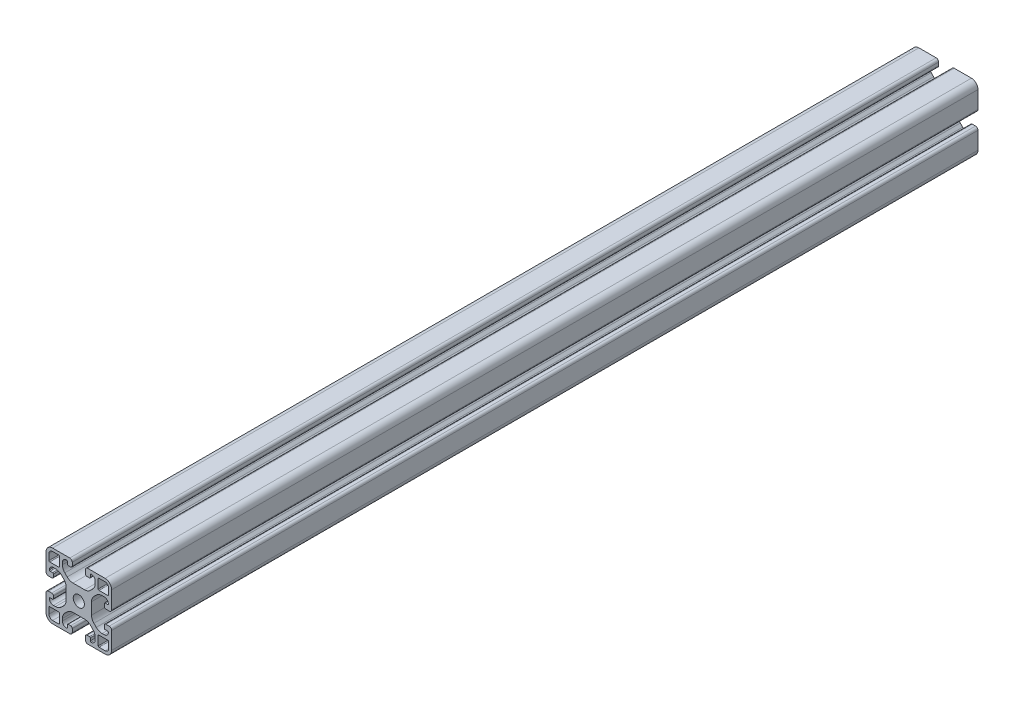
SolidWorks part; units mm, degrees
ref_plane "Plan de face" through (0, 0, 0) normal (0, 0, 1) x (1, 0, 0)
ref_plane "Plan de dessus" through (0, 0, 0) normal (0, 1, 0) x (1, 0, 0)
ref_plane "Plan de droite" through (0, 0, 0) normal (1, 0, 0) x (0, 0, -1)
ref_plane "Plan1" through (0, 0, -30) normal (0, 0, -1) x (-1, 0, 0)
sketch "Esquisse1" plane through (0, 0, -30) normal (0, 0, -1) x (-1, 0, 0)
  line B0 (-4.5, 15) -> (-4.5, 13.5)
  line B1 (-4, 13) -> (-2.5, 13)
  line B2 (-4.5, 10) -> (-5.8076, 10)
  line B3 (-9.3431, 11.4645) -> (-10.7855, 12.9069)
  line B4 (-12.25, 16.4424) -> (-12.25, 23.5576)
  line B5 (-10.7855, 27.0931) -> (-9.3431, 28.5355)
  line B6 (-5.8076, 30) -> (-4.5, 30)
  line B7 (-2.5, 27) -> (-4, 27)
  line B8 (-4.5, 26.5) -> (-4.5, 25)
  line B9 (-3.5, 24) -> (-1.5, 24)
  line B10 (0, 25.5) -> (0, 36)
  line B11 (-4, 40) -> (-14.5, 40)
  line B12 (-16, 38.5) -> (-16, 36.5)
  line B13 (-15, 35.5) -> (-13.5, 35.5)
  line B14 (-13, 36) -> (-13, 37.5)
  line B15 (-10, 35.5) -> (-10, 34.1924)
  line B16 (-11.4645, 30.6569) -> (-12.9069, 29.2145)
  line B17 (-16.4424, 27.75) -> (-23.5576, 27.75)
  line B18 (-27.0931, 29.2145) -> (-28.5355, 30.6569)
  line B19 (-30, 34.1924) -> (-30, 35.5)
  line B20 (-27, 37.5) -> (-27, 36)
  line B21 (-26.5, 35.5) -> (-25, 35.5)
  line B22 (-24, 36.5) -> (-24, 38.5)
  line B23 (-25.5, 40) -> (-36, 40)
  line B24 (-40, 36) -> (-40, 25.5)
  line B25 (-38.5, 24) -> (-36.5, 24)
  line B26 (-35.5, 25) -> (-35.5, 26.5)
  line B27 (-36, 27) -> (-37.5, 27)
  line B28 (-35.5, 30) -> (-34.1924, 30)
  line B29 (-30.6569, 28.5355) -> (-29.2145, 27.0931)
  line B30 (-27.75, 23.5576) -> (-27.75, 16.4424)
  line B31 (-29.2145, 12.9069) -> (-30.6569, 11.4645)
  line B32 (-34.1924, 10) -> (-35.5, 10)
  line B33 (-37.5, 13) -> (-36, 13)
  line B34 (-35.5, 13.5) -> (-35.5, 15)
  line B35 (-36.5, 16) -> (-38.5, 16)
  line B36 (-40, 14.5) -> (-40, 4)
  line B37 (-36, 0) -> (-25.5, 0)
  line B38 (-24, 1.5) -> (-24, 3.5)
  line B39 (-25, 4.5) -> (-26.5, 4.5)
  line B40 (-27, 4) -> (-27, 2.5)
  line B41 (-30, 4.5) -> (-30, 5.8076)
  line B42 (-28.5355, 9.3431) -> (-27.0931, 10.7855)
  line B43 (-23.5576, 12.25) -> (-16.4424, 12.25)
  line B44 (-12.9069, 10.7855) -> (-11.4645, 9.3431)
  line B45 (-10, 5.8076) -> (-10, 4.5)
  line B46 (-13, 2.5) -> (-13, 4)
  line B47 (-13.5, 4.5) -> (-15, 4.5)
  line B48 (-16, 3.5) -> (-16, 1.5)
  line B49 (-14.5, 0) -> (-4, 0)
  line B50 (0, 4) -> (0, 14.5)
  line B51 (-1.5, 16) -> (-3.5, 16)
  line B52 (-4, 1.8) -> (-7.7, 1.8)
  line B53 (-8.2, 2.3) -> (-8.2, 7.7)
  line B54 (-7.7, 8.2) -> (-2.3, 8.2)
  line B55 (-1.8, 7.7) -> (-1.8, 4)
  line B56 (-38.2, 4) -> (-38.2, 7.7)
  line B57 (-37.7, 8.2) -> (-32.3, 8.2)
  line B58 (-31.8, 7.7) -> (-31.8, 2.3)
  line B59 (-32.3, 1.8) -> (-36, 1.8)
  line B60 (-36, 38.2) -> (-32.3, 38.2)
  line B61 (-31.8, 37.7) -> (-31.8, 32.3)
  line B62 (-32.3, 31.8) -> (-37.7, 31.8)
  line B63 (-38.2, 32.3) -> (-38.2, 36)
  line B64 (-1.8, 36) -> (-1.8, 32.3)
  line B65 (-2.3, 31.8) -> (-7.7, 31.8)
  line B66 (-8.2, 32.3) -> (-8.2, 37.7)
  line B67 (-7.7, 38.2) -> (-4, 38.2)
  arc B68 (-4.5, 13.5) -> (-4, 13) centre (-4, 13.5) ccw
  arc B69 (-2.5, 13) -> (-2, 12.5) centre (-2.5, 12.5) cw
  arc B70 (-2, 12.5) -> (-4.5, 10) centre (-4.5, 12.5) cw
  arc B71 (-5.8076, 10) -> (-9.3431, 11.4645) centre (-5.8076, 15) cw
  arc B72 (-10.7855, 12.9069) -> (-12.25, 16.4424) centre (-7.25, 16.4424) cw
  arc B73 (-12.25, 23.5576) -> (-10.7855, 27.0931) centre (-7.25, 23.5576) cw
  arc B74 (-9.3431, 28.5355) -> (-5.8076, 30) centre (-5.8076, 25) cw
  arc B75 (-4.5, 30) -> (-2, 27.5) centre (-4.5, 27.5) cw
  arc B76 (-2, 27.5) -> (-2.5, 27) centre (-2.5, 27.5) cw
  arc B77 (-4, 27) -> (-4.5, 26.5) centre (-4, 26.5) ccw
  arc B78 (-4.5, 25) -> (-3.5, 24) centre (-3.5, 25) ccw
  arc B79 (-1.5, 24) -> (0, 25.5) centre (-1.5, 25.5) ccw
  arc B80 (0, 36) -> (-4, 40) centre (-4, 36) ccw
  arc B81 (-14.5, 40) -> (-16, 38.5) centre (-14.5, 38.5) ccw
  arc B82 (-16, 36.5) -> (-15, 35.5) centre (-15, 36.5) ccw
  arc B83 (-13.5, 35.5) -> (-13, 36) centre (-13.5, 36) ccw
  arc B84 (-13, 37.5) -> (-12.5, 38) centre (-12.5, 37.5) cw
  arc B85 (-12.5, 38) -> (-10, 35.5) centre (-12.5, 35.5) cw
  arc B86 (-10, 34.1924) -> (-11.4645, 30.6569) centre (-15, 34.1924) cw
  arc B87 (-12.9069, 29.2145) -> (-16.4424, 27.75) centre (-16.4424, 32.75) cw
  arc B88 (-23.5576, 27.75) -> (-27.0931, 29.2145) centre (-23.5576, 32.75) cw
  arc B89 (-28.5355, 30.6569) -> (-30, 34.1924) centre (-25, 34.1924) cw
  arc B90 (-30, 35.5) -> (-27.5, 38) centre (-27.5, 35.5) cw
  arc B91 (-27.5, 38) -> (-27, 37.5) centre (-27.5, 37.5) cw
  arc B92 (-27, 36) -> (-26.5, 35.5) centre (-26.5, 36) ccw
  arc B93 (-25, 35.5) -> (-24, 36.5) centre (-25, 36.5) ccw
  arc B94 (-24, 38.5) -> (-25.5, 40) centre (-25.5, 38.5) ccw
  arc B95 (-36, 40) -> (-40, 36) centre (-36, 36) ccw
  arc B96 (-40, 25.5) -> (-38.5, 24) centre (-38.5, 25.5) ccw
  arc B97 (-36.5, 24) -> (-35.5, 25) centre (-36.5, 25) ccw
  arc B98 (-35.5, 26.5) -> (-36, 27) centre (-36, 26.5) ccw
  arc B99 (-37.5, 27) -> (-38, 27.5) centre (-37.5, 27.5) cw
  arc B100 (-38, 27.5) -> (-35.5, 30) centre (-35.5, 27.5) cw
  arc B101 (-34.1924, 30) -> (-30.6569, 28.5355) centre (-34.1924, 25) cw
  arc B102 (-29.2145, 27.0931) -> (-27.75, 23.5576) centre (-32.75, 23.5576) cw
  arc B103 (-27.75, 16.4424) -> (-29.2145, 12.9069) centre (-32.75, 16.4424) cw
  arc B104 (-30.6569, 11.4645) -> (-34.1924, 10) centre (-34.1924, 15) cw
  arc B105 (-35.5, 10) -> (-38, 12.5) centre (-35.5, 12.5) cw
  arc B106 (-38, 12.5) -> (-37.5, 13) centre (-37.5, 12.5) cw
  arc B107 (-36, 13) -> (-35.5, 13.5) centre (-36, 13.5) ccw
  arc B108 (-35.5, 15) -> (-36.5, 16) centre (-36.5, 15) ccw
  arc B109 (-38.5, 16) -> (-40, 14.5) centre (-38.5, 14.5) ccw
  arc B110 (-40, 4) -> (-36, 0) centre (-36, 4) ccw
  arc B111 (-25.5, 0) -> (-24, 1.5) centre (-25.5, 1.5) ccw
  arc B112 (-24, 3.5) -> (-25, 4.5) centre (-25, 3.5) ccw
  arc B113 (-26.5, 4.5) -> (-27, 4) centre (-26.5, 4) ccw
  arc B114 (-27, 2.5) -> (-27.5, 2) centre (-27.5, 2.5) cw
  arc B115 (-27.5, 2) -> (-30, 4.5) centre (-27.5, 4.5) cw
  arc B116 (-30, 5.8076) -> (-28.5355, 9.3431) centre (-25, 5.8076) cw
  arc B117 (-27.0931, 10.7855) -> (-23.5576, 12.25) centre (-23.5576, 7.25) cw
  arc B118 (-16.4424, 12.25) -> (-12.9069, 10.7855) centre (-16.4424, 7.25) cw
  arc B119 (-11.4645, 9.3431) -> (-10, 5.8076) centre (-15, 5.8076) cw
  arc B120 (-10, 4.5) -> (-12.5, 2) centre (-12.5, 4.5) cw
  arc B121 (-12.5, 2) -> (-13, 2.5) centre (-12.5, 2.5) cw
  arc B122 (-13, 4) -> (-13.5, 4.5) centre (-13.5, 4) ccw
  arc B123 (-15, 4.5) -> (-16, 3.5) centre (-15, 3.5) ccw
  arc B124 (-16, 1.5) -> (-14.5, 0) centre (-14.5, 1.5) ccw
  arc B125 (-4, 0) -> (0, 4) centre (-4, 4) ccw
  arc B126 (0, 14.5) -> (-1.5, 16) centre (-1.5, 14.5) ccw
  arc B127 (-3.5, 16) -> (-4.5, 15) centre (-3.5, 15) ccw
  circle B128 centre (-20, 20) radius 3.4
  arc B129 (-1.8, 4) -> (-4, 1.8) centre (-4, 4) cw
  arc B130 (-7.7, 1.8) -> (-8.2, 2.3) centre (-7.7, 2.3) cw
  arc B131 (-8.2, 7.7) -> (-7.7, 8.2) centre (-7.7, 7.7) cw
  arc B132 (-2.3, 8.2) -> (-1.8, 7.7) centre (-2.3, 7.7) cw
  arc B133 (-36, 1.8) -> (-38.2, 4) centre (-36, 4) cw
  arc B134 (-38.2, 7.7) -> (-37.7, 8.2) centre (-37.7, 7.7) cw
  arc B135 (-32.3, 8.2) -> (-31.8, 7.7) centre (-32.3, 7.7) cw
  arc B136 (-31.8, 2.3) -> (-32.3, 1.8) centre (-32.3, 2.3) cw
  arc B137 (-38.2, 36) -> (-36, 38.2) centre (-36, 36) cw
  arc B138 (-32.3, 38.2) -> (-31.8, 37.7) centre (-32.3, 37.7) cw
  arc B139 (-31.8, 32.3) -> (-32.3, 31.8) centre (-32.3, 32.3) cw
  arc B140 (-37.7, 31.8) -> (-38.2, 32.3) centre (-37.7, 32.3) cw
  arc B141 (-4, 38.2) -> (-1.8, 36) centre (-4, 36) cw
  arc B142 (-1.8, 32.3) -> (-2.3, 31.8) centre (-2.3, 32.3) cw
  arc B143 (-7.7, 31.8) -> (-8.2, 32.3) centre (-7.7, 32.3) cw
  arc B144 (-8.2, 37.7) -> (-7.7, 38.2) centre (-7.7, 37.7) cw
sketch_block_instance "Bloc1-1"
sketch_block "Bloc1"
extrude "Boss.-Extru.1" add sketch "Esquisse1" against normal blind 528
